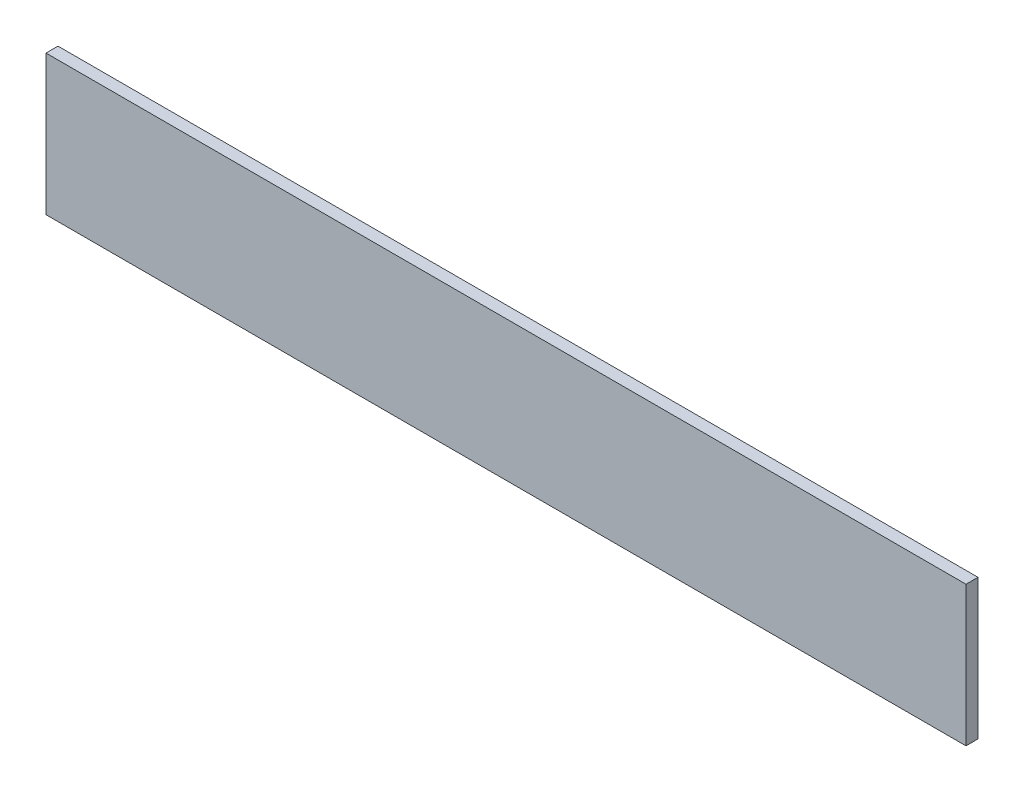
SolidWorks part; units mm, degrees
ref_plane "Front Plane" through (0, 0, 0) normal (0, 0, 1) x (1, 0, 0)
ref_plane "Top Plane" through (0, 0, 0) normal (0, 1, 0) x (1, 0, 0)
ref_plane "Right Plane" through (0, 0, 0) normal (1, 0, 0) x (0, 0, -1)
sketch "Sketch1" plane through (0, 0, 0) normal (0, 0, 1) x (1, 0, 0)
  line L1 (-115, -17.5) -> (115, -17.5)
  line L2 (-115, -17.5) -> (-115, 17.5)
  line L3 (-115, 17.5) -> (115, 17.5)
  line L4 (115, -17.5) -> (115, 17.5)
  line L5 (-115, -17.5) -> (115, 17.5) construction
  line L6 (-115, 17.5) -> (115, -17.5) construction
  point P0 (0, 0)
  dimension "D1" = 35
  dimension "D2" = 230
extrude "Boss-Extrude1" add sketch "Sketch1" along normal blind 3
equation "\"PCLength\"= 320mm'Length across I/O from PS to GPU"
equation "\"PCWidth\"= 242mm'Distance of longest part parallel to GPU(ussually GPU)"
equation "\"PCHeight\"= 172mm'Tallest point with mobo laying flat"
equation "\"WallThickness\"= 9mm'Thickness of each outer tank wall"
equation "\"ThermoBarrierThickness\"= 3mm'Thickness of barrier between hot side and cold side"
equation "\"HotSideGap\"= 35mm'Space in the hot side for a pump"
equation "\"PCClearance\"= 30mm'Clearance from top of tank to top of PC"
equation "\"RadiatorHeight\"= 275mm'Final Height from ground of radiators"
equation "\"AirflowGap\"= 36mm'Distance between radiators and tank for airflow"
equation "\"VolumeSubtraction\"= 230mm"
equation "\"D1@Sketch1\"=\"HotSideGap\""
equation "\"D2@Sketch1\"=\"VolumeSubtraction\""
equation "\"D1@Boss-Extrude1\"=\"ThermoBarrierThickness\""
